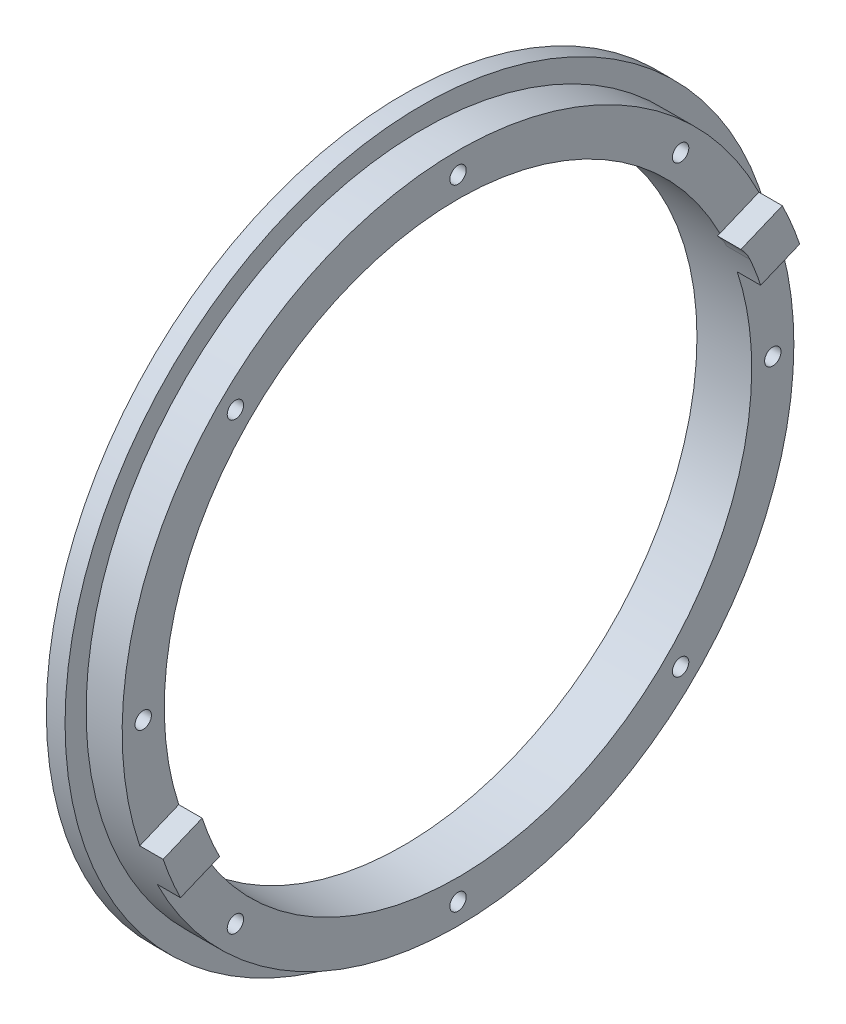
SolidWorks part; units mm, degrees
ref_plane "前视基准面" through (0, 0, 0) normal (0, 0, 1) x (1, 0, 0)
ref_plane "上视基准面" through (0, 0, 0) normal (0, 1, 0) x (1, 0, 0)
ref_plane "右视基准面" through (0, 0, 0) normal (1, 0, 0) x (0, 0, -1)
other "Configuration Table"
sketch "草图2" plane through (0, 0, 0) normal (0, 0, 1) x (1, 0, 0)
  line L0 (-30.3, 71.75) -> (-43, 71.75)
  line L1 (-43, 71.75) -> (-43, 76.25)
  line L2 (-43, 76.25) -> (-47, 76.25)
  line L3 (-47, 76.25) -> (-47, 62.75)
  line L4 (-47, 62.75) -> (-30.3, 62.75)
  line L5 (-30.3, 62.75) -> (-30.3, 71.75)
  line L6 (-47, 0) -> (-30.3, 0) construction
  dimension "D1" = 4
  dimension "D2" = 16.7
  dimension "D3" = 62.75
  dimension "D4" = 71.75
  dimension "D5" = 76.25
revolve "旋转1" add sketch "草图2" angle 360 about L6
sketch "草图3" plane through (-30.3, 0, 0) normal (1, 0, 0) x (0, 0, -1)
  line L0 (55.944, 28.4224) -> (64.2807, 31.8756)
  line L1 (-67.9928, -22.9139) -> (-59.656, -19.4607)
  arc A0 (-59.656, -19.4607) -> (55.944, 28.4224) centre (0, 0) cw
  arc A1 (64.2807, 31.8756) -> (-67.9928, -22.9139) centre (0, 0) ccw
  circle A2 centre (0, 0) radius 71.75 construction
  dimension "D1" = 62.75
  dimension "D2" = 71.75
  dimension "D3" = 55.944
  dimension "D4" = 64.2807
  dimension "D5" = 59.656
  dimension "D6" = 67.9928
  dimension "D7" = 28.4224
  dimension "D8" = 31.8756
extrude "切除-拉伸1" cut sketch "草图3" against normal blind 5
sketch "草图4" plane through (-30.3, 0, 0) normal (1, 0, 0) x (0, 0, -1)
  line L0 (-55.944, -28.4224) -> (-64.2807, -31.8756)
  line L1 (67.9928, 22.9139) -> (59.656, 19.4607)
  arc A0 (-64.2807, -31.8756) -> (67.9928, 22.9139) centre (0, 0) ccw
  arc A1 (59.656, 19.4607) -> (-55.944, -28.4224) centre (0, 0) cw
  dimension "D1" = 71.75
  dimension "D2" = 62.75
  dimension "D3" = 3.712
  dimension "D4" = 59.656
  dimension "D5" = 119.3121
  dimension "D6" = 127.6488
  dimension "D7" = 4.6247
  dimension "D8" = 8.9616
extrude "切除-拉伸2" cut sketch "草图4" against normal blind 5
ref_plane "基准面2" through (-30.3, 0, 0) normal (1, 0, 0) x (0, 0, -1)
sketch "草图5" plane through (-30.3, 0, 0) normal (1, 0, 0) x (0, 0, -1)
  line L0 (55.944, 28.4224) -> (55.4317, 28.2102)
  arc A0 (55.4317, 28.2102) -> (57.3991, 25.3557) centre (48.8921, 21.5978) cw
  arc A1 (57.3991, 25.3557) -> (55.944, 28.4224) centre (0, 0) ccw
  dimension "D1" = 9.3
  dimension "D2" = 62.75
  dimension "D3" = 1.4551
  dimension "D4" = 1.9673
  dimension "D5" = 8.507
extrude "凸台-拉伸1" add sketch "草图5" against normal blind 5
hole_wizard "孔1" positions "草图7" profile "草图6" legacy
sketch "草图7" plane through (-47, 0, 0) normal (-1, 0, 0) x (0, 0, 1)
  point P0 (-67.25, 0)
sketch "草图6" plane through (-47, 0, -67.25) normal (0, 1, 0) x (0, 0, 1)
  line L0 (0, 0) -> (0, 16.7)
  line L1 (0, 16.7) -> (1.75, 16.7)
  line L2 (1.75, 16.7) -> (1.75, 2)
  line L3 (1.75, 2) -> (3.25, 2)
  line L4 (3.25, 2) -> (3.25, 0)
  line L5 (3.25, 0) -> (0, 0)
  line L6 (0, 110) -> (0, -10) construction
  dimension "直径" = 3.5
  dimension "深度" = 16.7
  dimension "柱坑直径" = 6.5
  dimension "柱坑深度" = 2
hole_wizard "孔2" positions "草图9" profile "草图8" legacy
sketch "草图9" plane through (-47, 0, 0) normal (-1, 0, 0) x (0, 0, 1)
  point P0 (-47.5529, 47.5529)
sketch "草图8" plane through (-47, 47.5529, -47.5529) normal (0, 1, 0) x (0, 0, 1)
  line L0 (0, 0) -> (0, 16.7)
  line L1 (0, 16.7) -> (1.75, 16.7)
  line L2 (1.75, 16.7) -> (1.75, 2)
  line L3 (1.75, 2) -> (3.25, 2)
  line L4 (3.25, 2) -> (3.25, 0)
  line L5 (3.25, 0) -> (0, 0)
  line L6 (0, 110) -> (0, -10) construction
  dimension "直径" = 3.5
  dimension "深度" = 16.7
  dimension "柱坑直径" = 6.5
  dimension "柱坑深度" = 2
hole_wizard "孔3" positions "草图11" profile "草图10" legacy
sketch "草图11" plane through (-47, 0, 0) normal (-1, 0, 0) x (0, 0, 1)
  point P0 (0, 67.25)
sketch "草图10" plane through (-47, 67.25, 0) normal (0, 1, 0) x (0, 0, 1)
  line L0 (0, 0) -> (0, 16.7)
  line L1 (0, 16.7) -> (1.75, 16.7)
  line L2 (1.75, 16.7) -> (1.75, 2)
  line L3 (1.75, 2) -> (3.25, 2)
  line L4 (3.25, 2) -> (3.25, 0)
  line L5 (3.25, 0) -> (0, 0)
  line L6 (0, 110) -> (0, -10) construction
  dimension "直径" = 3.5
  dimension "深度" = 16.7
  dimension "柱坑直径" = 6.5
  dimension "柱坑深度" = 2
hole_wizard "孔4" positions "草图13" profile "草图12" legacy
sketch "草图13" plane through (-47, 0, 0) normal (-1, 0, 0) x (0, 0, 1)
  point P0 (47.5529, 47.5529)
sketch "草图12" plane through (-47, 47.5529, 47.5529) normal (0, 1, 0) x (0, 0, 1)
  line L0 (0, 0) -> (0, 16.7)
  line L1 (0, 16.7) -> (1.75, 16.7)
  line L2 (1.75, 16.7) -> (1.75, 2)
  line L3 (1.75, 2) -> (3.25, 2)
  line L4 (3.25, 2) -> (3.25, 0)
  line L5 (3.25, 0) -> (0, 0)
  line L6 (0, 110) -> (0, -10) construction
  dimension "直径" = 3.5
  dimension "深度" = 16.7
  dimension "柱坑直径" = 6.5
  dimension "柱坑深度" = 2
hole_wizard "孔5" positions "草图15" profile "草图14" legacy
sketch "草图15" plane through (-47, 0, 0) normal (-1, 0, 0) x (0, 0, 1)
  point P0 (67.25, 0)
sketch "草图14" plane through (-47, 0, 67.25) normal (0, 1, 0) x (0, 0, 1)
  line L0 (0, 0) -> (0, 16.7)
  line L1 (0, 16.7) -> (1.75, 16.7)
  line L2 (1.75, 16.7) -> (1.75, 2)
  line L3 (1.75, 2) -> (3.25, 2)
  line L4 (3.25, 2) -> (3.25, 0)
  line L5 (3.25, 0) -> (0, 0)
  line L6 (0, 110) -> (0, -10) construction
  dimension "直径" = 3.5
  dimension "深度" = 16.7
  dimension "柱坑直径" = 6.5
  dimension "柱坑深度" = 2
hole_wizard "孔6" positions "草图17" profile "草图16" legacy
sketch "草图17" plane through (-47, 0, 0) normal (-1, 0, 0) x (0, 0, 1)
  point P0 (47.5529, -47.5529)
sketch "草图16" plane through (-47, -47.5529, 47.5529) normal (0, 1, 0) x (0, 0, 1)
  line L0 (0, 0) -> (0, 16.7)
  line L1 (0, 16.7) -> (1.75, 16.7)
  line L2 (1.75, 16.7) -> (1.75, 2)
  line L3 (1.75, 2) -> (3.25, 2)
  line L4 (3.25, 2) -> (3.25, 0)
  line L5 (3.25, 0) -> (0, 0)
  line L6 (0, 110) -> (0, -10) construction
  dimension "直径" = 3.5
  dimension "深度" = 16.7
  dimension "柱坑直径" = 6.5
  dimension "柱坑深度" = 2
hole_wizard "孔7" positions "草图19" profile "草图18" legacy
sketch "草图19" plane through (-47, 0, 0) normal (-1, 0, 0) x (0, 0, 1)
  point P0 (0, -67.25)
sketch "草图18" plane through (-47, -67.25, 0) normal (0, 1, 0) x (0, 0, 1)
  line L0 (0, 0) -> (0, 16.7)
  line L1 (0, 16.7) -> (1.75, 16.7)
  line L2 (1.75, 16.7) -> (1.75, 2)
  line L3 (1.75, 2) -> (3.25, 2)
  line L4 (3.25, 2) -> (3.25, 0)
  line L5 (3.25, 0) -> (0, 0)
  line L6 (0, 110) -> (0, -10) construction
  dimension "直径" = 3.5
  dimension "深度" = 16.7
  dimension "柱坑直径" = 6.5
  dimension "柱坑深度" = 2
hole_wizard "孔8" positions "草图21" profile "草图20" legacy
sketch "草图21" plane through (-47, 0, 0) normal (-1, 0, 0) x (0, 0, 1)
  point P0 (-47.5529, -47.5529)
sketch "草图20" plane through (-47, -47.5529, -47.5529) normal (0, 1, 0) x (0, 0, 1)
  line L0 (0, 0) -> (0, 16.7)
  line L1 (0, 16.7) -> (1.75, 16.7)
  line L2 (1.75, 16.7) -> (1.75, 2)
  line L3 (1.75, 2) -> (3.25, 2)
  line L4 (3.25, 2) -> (3.25, 0)
  line L5 (3.25, 0) -> (0, 0)
  line L6 (0, 110) -> (0, -10) construction
  dimension "直径" = 3.5
  dimension "深度" = 16.7
  dimension "柱坑直径" = 6.5
  dimension "柱坑深度" = 2
